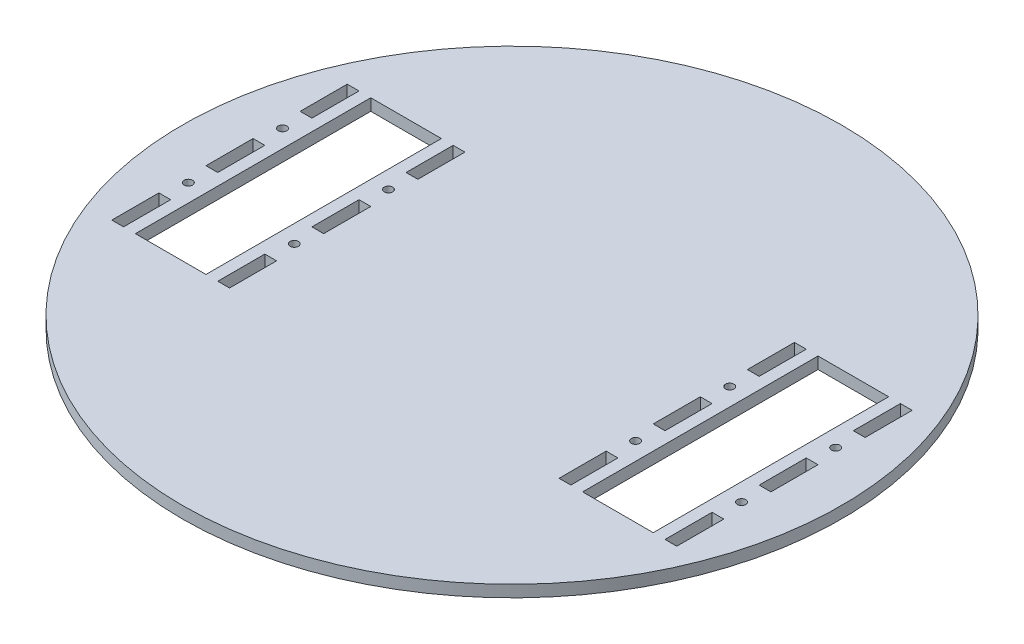
SolidWorks part; units mm, degrees
ref_plane "Front" through (0, 0, 0) normal (0, 0, 1) x (1, 0, 0)
ref_plane "Top" through (0, 0, 0) normal (0, 1, 0) x (1, 0, 0)
ref_plane "Right" through (0, 0, 0) normal (1, 0, 0) x (0, 0, -1)
sketch "Sketch1" plane through (0, 0, 0) normal (0, 1, 0) x (1, 0, 0)
  circle A0 centre (0, 0) radius 177.8
  dimension "D1" = 355.6
extrude "Boss-Extrude1" add sketch "Sketch1" along normal blind 6.35
sketch "Sketch2" plane through (0, 6.35, 0) normal (0, 1, 0) x (1, 0, 0)
  line L0 (0, 177.8) -> (0, -177.8) construction
  line L1 (-177.8, 0) -> (177.8, 0) construction
  line L2 (-120.65, 63.5) -> (-120.65, -63.5) construction
  line L3 (-139.7, 63.5) -> (-101.6, 63.5)
  line L4 (-139.7, 63.5) -> (-139.7, -63.5)
  line L5 (-139.7, -63.5) -> (-101.6, -63.5)
  line L6 (-101.6, 63.5) -> (-101.6, -63.5)
  line L7 (-139.7, 63.5) -> (-101.6, -63.5) construction
  line L8 (-139.7, -63.5) -> (-101.6, 63.5) construction
  line L9 (-149.225, 38.1) -> (-149.225, 12.7) construction
  line L10 (-152.4, 63.5) -> (-146.05, 63.5)
  line L11 (-152.4, 63.5) -> (-152.4, 38.1)
  line L12 (-152.4, 38.1) -> (-146.05, 38.1)
  line L13 (-146.05, 63.5) -> (-146.05, 38.1)
  line L14 (-152.4, 12.7) -> (-146.05, 12.7)
  line L15 (-152.4, 12.7) -> (-152.4, -12.7)
  line L16 (-152.4, -12.7) -> (-146.05, -12.7)
  line L17 (-146.05, 12.7) -> (-146.05, -12.7)
  line L18 (-152.4, 12.7) -> (-146.05, -12.7) construction
  line L19 (-152.4, -12.7) -> (-146.05, 12.7) construction
  line L20 (-152.4, 12.7) -> (-146.05, -12.7) construction
  line L21 (-152.4, -12.7) -> (-146.05, 12.7) construction
  line L22 (-149.225, -38.1) -> (-149.225, -12.7) construction
  line L25 (-146.05, -63.5) -> (-146.05, -38.1)
  line L26 (-152.4, -38.1) -> (-146.05, -38.1)
  line L27 (-152.4, -63.5) -> (-152.4, -38.1)
  line L28 (-152.4, -63.5) -> (-146.05, -63.5)
  line L29 (-92.075, -38.1) -> (-92.075, -12.7) construction
  line L30 (-88.9, -12.7) -> (-95.25, 12.7) construction
  line L31 (-88.9, 12.7) -> (-95.25, -12.7) construction
  line L32 (-88.9, -12.7) -> (-95.25, 12.7) construction
  line L33 (-88.9, 12.7) -> (-95.25, -12.7) construction
  line L34 (-92.075, 38.1) -> (-92.075, 12.7) construction
  line L35 (-88.9, -63.5) -> (-95.25, -63.5)
  line L36 (-88.9, -63.5) -> (-88.9, -38.1)
  line L37 (-88.9, -38.1) -> (-95.25, -38.1)
  line L38 (-95.25, -63.5) -> (-95.25, -38.1)
  line L39 (-88.9, -12.7) -> (-95.25, -12.7)
  line L40 (-88.9, 12.7) -> (-95.25, 12.7)
  line L41 (-95.25, 12.7) -> (-95.25, -12.7)
  line L43 (-88.9, 12.7) -> (-88.9, -12.7)
  line L45 (-95.25, 63.5) -> (-95.25, 38.1)
  line L46 (-88.9, 38.1) -> (-95.25, 38.1)
  line L47 (-88.9, 63.5) -> (-88.9, 38.1)
  line L48 (-88.9, 63.5) -> (-95.25, 63.5)
  line L49 (92.075, 38.1) -> (92.075, 12.7) construction
  line L50 (88.9, 12.7) -> (95.25, -12.7) construction
  line L51 (88.9, -12.7) -> (95.25, 12.7) construction
  line L52 (88.9, 12.7) -> (95.25, -12.7) construction
  line L53 (88.9, -12.7) -> (95.25, 12.7) construction
  line L54 (92.075, -38.1) -> (92.075, -12.7) construction
  line L55 (149.225, -38.1) -> (149.225, -12.7) construction
  line L56 (152.4, -12.7) -> (146.05, 12.7) construction
  line L57 (152.4, 12.7) -> (146.05, -12.7) construction
  line L58 (152.4, -12.7) -> (146.05, 12.7) construction
  line L59 (152.4, 12.7) -> (146.05, -12.7) construction
  line L60 (149.225, 38.1) -> (149.225, 12.7) construction
  line L61 (139.7, -63.5) -> (101.6, 63.5) construction
  line L62 (139.7, 63.5) -> (101.6, -63.5) construction
  line L63 (120.65, 63.5) -> (120.65, -63.5) construction
  line L64 (88.9, 63.5) -> (95.25, 63.5)
  line L65 (88.9, 63.5) -> (88.9, 38.1)
  line L66 (88.9, 38.1) -> (95.25, 38.1)
  line L67 (95.25, 63.5) -> (95.25, 38.1)
  line L68 (88.9, 12.7) -> (95.25, 12.7)
  line L69 (88.9, 12.7) -> (88.9, -12.7)
  line L70 (88.9, -12.7) -> (95.25, -12.7)
  line L71 (95.25, 12.7) -> (95.25, -12.7)
  line L74 (95.25, -63.5) -> (95.25, -38.1)
  line L75 (88.9, -38.1) -> (95.25, -38.1)
  line L76 (88.9, -63.5) -> (88.9, -38.1)
  line L77 (88.9, -63.5) -> (95.25, -63.5)
  line L78 (152.4, -63.5) -> (146.05, -63.5)
  line L79 (152.4, -63.5) -> (152.4, -38.1)
  line L80 (152.4, -38.1) -> (146.05, -38.1)
  line L81 (146.05, -63.5) -> (146.05, -38.1)
  line L82 (152.4, -12.7) -> (146.05, -12.7)
  line L83 (152.4, 12.7) -> (146.05, 12.7)
  line L84 (146.05, 12.7) -> (146.05, -12.7)
  line L86 (152.4, 12.7) -> (152.4, -12.7)
  line L88 (146.05, 63.5) -> (146.05, 38.1)
  line L89 (152.4, 38.1) -> (146.05, 38.1)
  line L90 (152.4, 63.5) -> (152.4, 38.1)
  line L91 (152.4, 63.5) -> (146.05, 63.5)
  line L92 (101.6, 63.5) -> (101.6, -63.5)
  line L93 (139.7, -63.5) -> (101.6, -63.5)
  line L94 (139.7, 63.5) -> (139.7, -63.5)
  line L95 (139.7, 63.5) -> (101.6, 63.5)
  circle A0 centre (0, 0) radius 177.8 construction
  circle A1 centre (-149.225, 25.4) radius 2.286
  circle A2 centre (-149.225, -25.4) radius 2.286
  circle A3 centre (-92.075, -25.4) radius 2.286
  circle A4 centre (-92.075, 25.4) radius 2.286
  circle A5 centre (92.075, 25.4) radius 2.286
  circle A6 centre (92.075, -25.4) radius 2.286
  circle A7 centre (149.225, -25.4) radius 2.286
  circle A8 centre (149.225, 25.4) radius 2.286
  point P7 (-120.65, 0)
  point P18 (-149.225, 0)
  point P55 (-92.075, 0)
  point P102 (92.075, 0)
  point P103 (149.225, 0)
  point P104 (120.65, 0)
  dimension "D8" = 4.572
  dimension "D1" = 38.1
  dimension "D2" = 127
  dimension "D3" = 101.6
  dimension "D4" = 25.4
  dimension "D5" = 6.35
  dimension "D6" = 25.4
  dimension "D7" = 6.35
extrude "Cut-Extrude1" cut sketch "Sketch2" against normal through all
